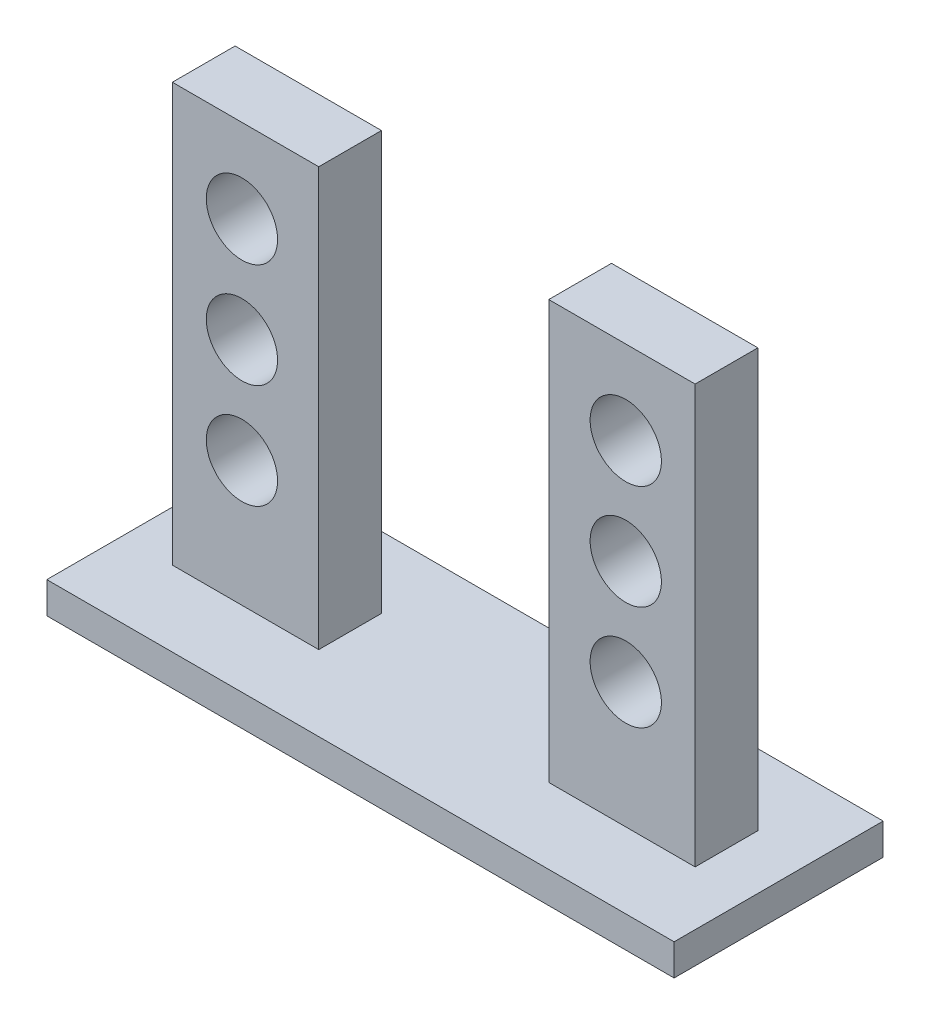
SolidWorks part; units mm, degrees
ref_plane "Front Plane" through (0, 0, 0) normal (0, 0, 1) x (1, 0, 0)
ref_plane "Top Plane" through (0, 0, 0) normal (0, 1, 0) x (1, 0, 0)
ref_plane "Right Plane" through (0, 0, 0) normal (1, 0, 0) x (0, 0, -1)
sketch "Sketch1" plane through (0, 0, 0) normal (0, 1, 0) x (1, 0, 0)
  line L2 (-5.7895, 5) -> (-15.7895, 5)
  line L3 (-15.7895, 5) -> (-15.7895, -5)
  line L4 (-23.9474, 0) -> (25.2632, 0) construction
  line L5 (-5.7895, -5) -> (-15.7895, -5)
  line L8 (-5.7895, 5) -> (4.2105, 5)
  line L10 (4.2105, -5) -> (14.2105, -5)
  line L11 (14.2105, 5) -> (14.2105, -5)
  line L12 (4.2105, 5) -> (14.2105, 5)
  line L14 (4.2105, -5) -> (-5.7895, -5)
  point P9 (-15.7895, 0)
  point P14 (14.2105, 0)
  dimension "D2" = 5
extrude "Boss-Extrude1" add sketch "Sketch1" against normal blind 1.5
sketch "Sketch3" plane through (0, 0, 0) normal (0, 1, 0) x (1, 0, 0)
  line L6 (-13.3867, -1.3974) -> (-6.3867, -1.3974)
  line L7 (-13.3867, -1.3974) -> (-13.3867, 1.6026)
  line L8 (-13.3867, 1.6026) -> (-6.3867, 1.6026)
  line L9 (-6.3867, -1.3974) -> (-6.3867, 1.6026)
  line L10 (-13.3867, -1.3974) -> (-6.3867, 1.6026) construction
  line L11 (-13.3867, 1.6026) -> (-6.3867, -1.3974) construction
  line L12 (4.6133, -1.3974) -> (11.6133, -1.3974)
  line L13 (4.6133, -1.3974) -> (4.6133, 1.6026)
  line L14 (4.6133, 1.6026) -> (11.6133, 1.6026)
  line L15 (11.6133, -1.3974) -> (11.6133, 1.6026)
  line L16 (4.6133, -1.3974) -> (11.6133, 1.6026) construction
  line L17 (4.6133, 1.6026) -> (11.6133, -1.3974) construction
  point P0 (-9.8867, 0.1026)
  point P5 (8.1133, 0.1026)
  dimension "D1" = 7
  dimension "D2" = 3
  dimension "D3" = 11
  dimension "D4" = 7
  dimension "D5" = 3
  dimension "D6" = 0
extrude "Boss-Extrude2" add sketch "Sketch3" along normal blind 20
sketch "Sketch4" plane through (0, 0, 0) normal (0, 0, 1) x (1, 0, 0)
  line L0 (-13.3867, 20) -> (-6.3867, 20) construction
  line L1 (4.6133, 20) -> (11.6133, 20) construction
  circle A0 centre (-10.0595, 16) radius 1.705
  circle A1 centre (8.2952, 16) radius 1.705
  dimension "D1" = 3.41
  dimension "D2" = 3.41
  dimension "D4" = 4
  dimension "D3" = 4
extrude "Cut-Extrude1" cut sketch "Sketch4" along normal mid plane 10
pattern_linear "LPattern1" count 3 spacing 5 along (0, -1, 0) of "Cut-Extrude1"
